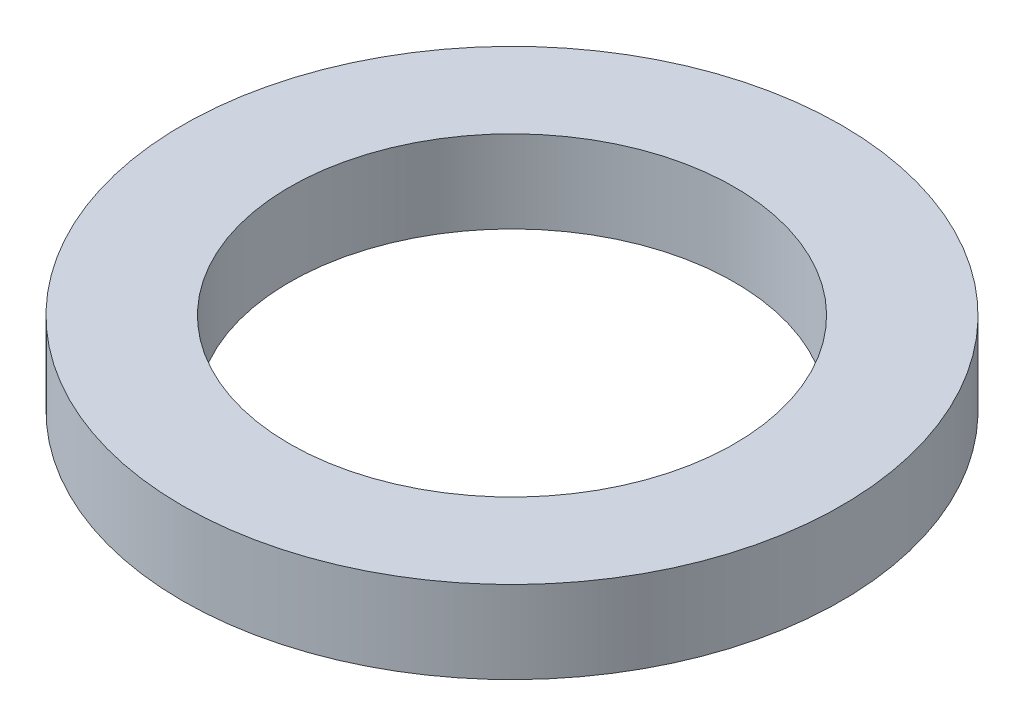
SolidWorks part; units mm, degrees
ref_plane "Front Plane" through (0, 0, 0) normal (0, 0, 1) x (1, 0, 0)
ref_plane "Top Plane" through (0, 0, 0) normal (0, 1, 0) x (1, 0, 0)
ref_plane "Right Plane" through (0, 0, 0) normal (1, 0, 0) x (0, 0, -1)
sketch "Sketch1" plane through (0, 0, 0) normal (0, 1, 0) x (1, 0, 0)
  circle A0 centre (0, 0) radius 4
  circle A1 centre (0, 0) radius 2.7
  dimension "D1" = 8
  dimension "D2" = 5.4
extrude "Boss-Extrude1" add sketch "Sketch1" along normal blind 1
